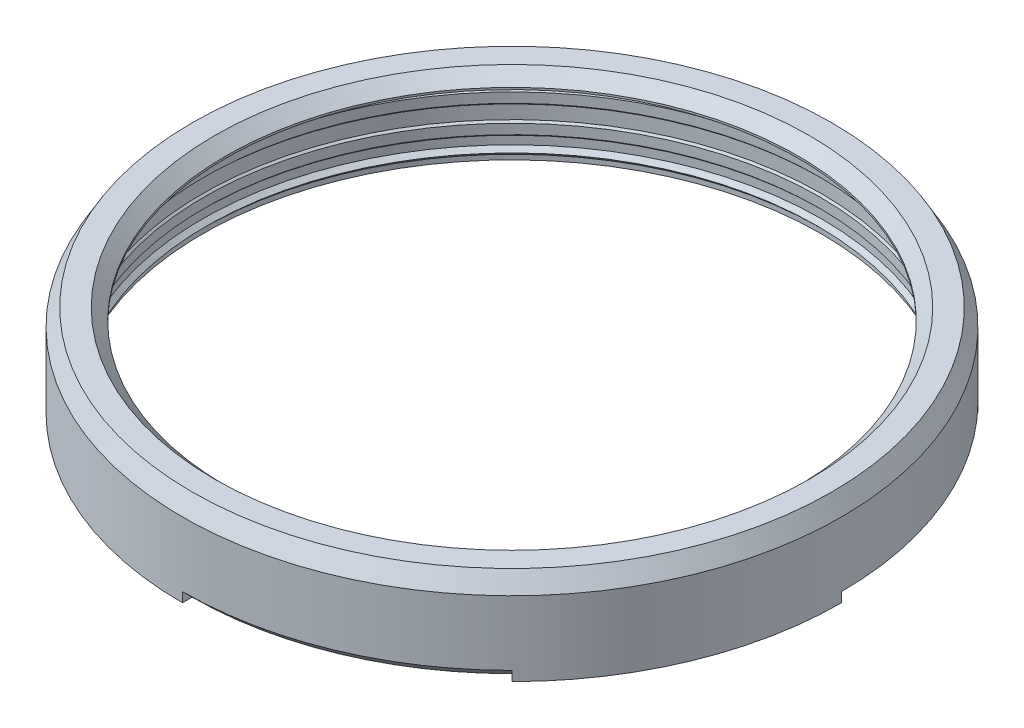
SolidWorks part; units mm, degrees
ref_plane "前视基准面" through (0, 0, 0) normal (0, 0, 1) x (1, 0, 0)
ref_plane "上视基准面" through (0, 0, 0) normal (0, 1, 0) x (1, 0, 0)
ref_plane "右视基准面" through (0, 0, 0) normal (1, 0, 0) x (0, 0, -1)
sketch "草图1" plane through (0, 0, 0) normal (0, 1, 0) x (1, 0, 0)
  circle A0 centre (0, 0) radius 34
  dimension "D1" = 68
extrude "凸台-拉伸1" add sketch "草图1" along normal blind 2
sketch "草图2" plane through (0, 0, 0) normal (-0.866, 0, 0.5) x (0.5, 0, 0.866)
  line L0 (31.8, -8) -> (33, -8) construction
  line L2 (0, 0) -> (0, 7.5922) construction
  line L3 (31.8, -8) -> (31.8, -7.5) construction
  line L12 (31.93, -8) -> (31.93, -7.5)
  line L13 (31.93, -7.5) -> (31.505, -7.075)
  line L14 (31.505, -7.075) -> (31.93, -6.65)
  line L15 (31.93, -6.65) -> (31.93, -5.8)
  line L16 (31.93, -5.8) -> (31.74, -5.61)
  line L17 (31.74, -5.61) -> (31.74, -4.59)
  line L18 (31.74, -4.59) -> (31.93, -4.4)
  line L19 (31.93, -4.4) -> (31.93, -3)
  line L20 (31.93, -3) -> (31.74, -2.81)
  line L21 (31.74, -2.81) -> (31.74, -1.79)
  line L22 (31.74, -1.79) -> (31.93, -1.6)
  line L23 (31.93, -1.6) -> (31.93, -1.4)
  line L24 (30.53, 0) -> (34, 0)
  line L25 (34, 0) -> (34, -8)
  line L26 (34, -8) -> (31.93, -8)
  arc A1 (31.93, -1.4) -> (30.53, 0) centre (30.53, -1.4) ccw
  dimension "D9" = 1.4
  dimension "D1" = 2.26
  dimension "D2" = 8
  dimension "D3" = 0.5
  dimension "D4" = 0.85
  dimension "D5" = 1.4
  dimension "D6" = 1.02
  dimension "D7" = 1.02
  dimension "D8" = 0.2
  dimension "D10" = 135
  dimension "D11" = 0.13
revolve "旋转1" add sketch "草图2" angle 360 about L2
sketch "草图3" plane through (0, 2, 0) normal (0, 1, 0) x (1, 0, 0)
  circle A0 centre (0, 0) radius 29.5
  circle A1 centre (0, 0) radius 34 construction
  dimension "D1" = 4.5
extrude "切除-拉伸1" cut sketch "草图3" against normal through all
sketch "草图4" plane through (0, 2, 0) normal (0, 1, 0) x (1, 0, 0)
  circle A1 centre (0, 0) radius 34
  circle A2 centre (0, 0) radius 34
  dimension "D1" = 0
extrude "切除-拉伸2" cut sketch "草图4" against normal blind 0.6
chamfer "倒角2" distance 1.732 angle 30 1 edges at (0, 1.4, 34)
chamfer "倒角3" distance 1.2 angle 45 1 edges at (0, 1.4, 29.5)
sketch "草图5" plane through (0, 0, 0) normal (0, 0, 1) x (1, 0, 0)
  line L0 (34, -8) -> (34, -7)
  line L1 (34, -7) -> (33, -8)
  line L2 (-34, -8) -> (34, -8) construction
  line L3 (33, -8) -> (34, -8)
  line L4 (0, 0) -> (0, 11.2262) construction
  dimension "D1" = 1
  dimension "D2" = 1
revolve "切除-旋转1" cut sketch "草图5" angle 45 about L4
pattern_circular "阵列(圆周)1" count 4 over 360 about axis through (0, 0, 0) along (0, 1, 0) of "切除-旋转1"
sketch "草图6" plane through (0, 0, 0) normal (0, -1, 0) x (1, 0, 0)
  circle A0 centre (0, 0) radius 30.32
  circle A1 centre (0, 0) radius 30.78
  circle A2 centre (0, 0) radius 29.5 construction
  dimension "D1" = 0.82
  dimension "D2" = 0.46
extrude "凸台-拉伸2" add sketch "草图6" along normal blind 0.5
